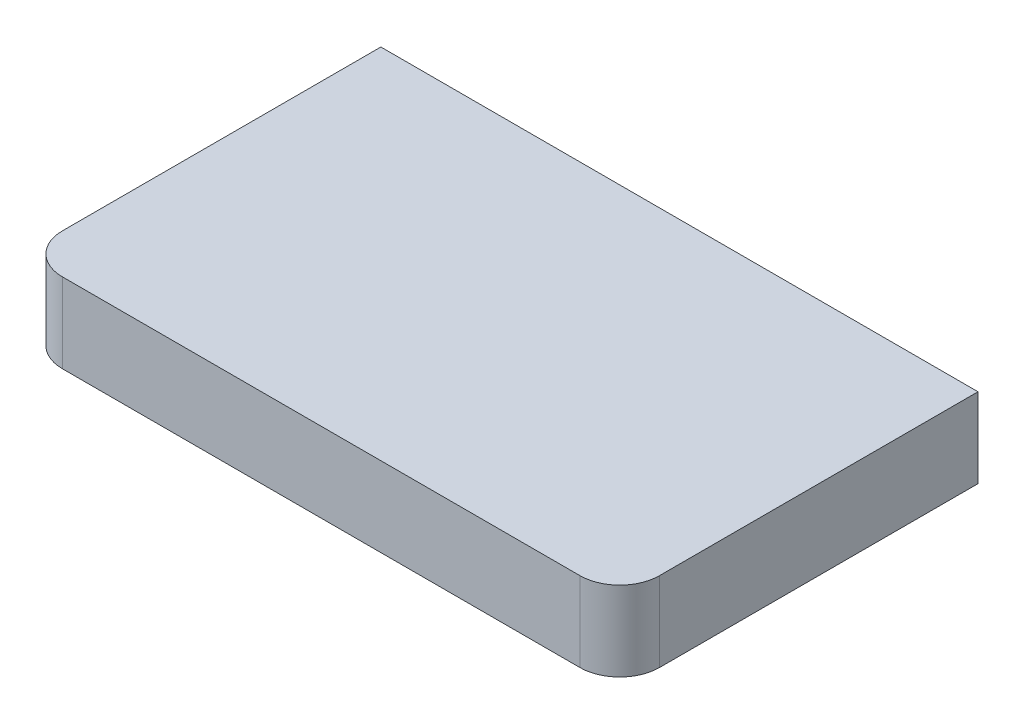
SolidWorks part; units mm, degrees
ref_plane "Front Plane" through (0, 0, 0) normal (0, 0, 1) x (1, 0, 0)
ref_plane "Top Plane" through (0, 0, 0) normal (0, 1, 0) x (1, 0, 0)
ref_plane "Right Plane" through (0, 0, 0) normal (1, 0, 0) x (0, 0, -1)
sketch "Sketch1" plane through (0, 0, 0) normal (1, 0, 0) x (0, 0, -1)
  line L2 (0, 0) -> (-90, 0)
  line L3 (-90, 0) -> (-90, 20)
  line L4 (-90, 20) -> (0, 20)
  line L6 (0, 20) -> (0, 0)
  dimension "D2" = 20
  dimension "D3" = 90
extrude "Boss-Extrude1" add sketch "Sketch1" against normal blind 150
sketch "Sketch2" plane through (0, 0, 0) normal (0, -1, 0) x (1, 0, 0)
  line L0 (-150, 90) -> (0, 90) construction
  line L3 (0, 90) -> (0, 0) construction
  circle A0 centre (-50, 62.75) radius 15
  circle A1 centre (-100, 62.75) radius 15
  dimension "D1" = 27.25
  dimension "D2" = 30
  dimension "D3" = 50
  dimension "D4" = 50
extrude "Cut-Extrude1" cut sketch "Sketch2" against normal blind 10 and the other way through all
sketch "Sketch4" plane through (0, 0, 0) normal (0, 0, -1) x (-1, 0, 0)
  line L1 (150, 0) -> (150, 20) construction
  line L2 (150, 0) -> (0, 0) construction
  circle A0 centre (15, 10) radius 5
  circle A1 centre (75, 10) radius 5
  circle A2 centre (135, 10) radius 5
  point P11 (150, 10)
  point P12 (75, 0)
  dimension "D3" = 10
  dimension "D1" = 60
  dimension "D2" = 60
extrude "Cut-Extrude3" cut sketch "Sketch4" against normal blind 70 and the other way through all
fillet "Fillet1" radius 10 2 edges at (-150, 10, 90) (0, 10, 90)
